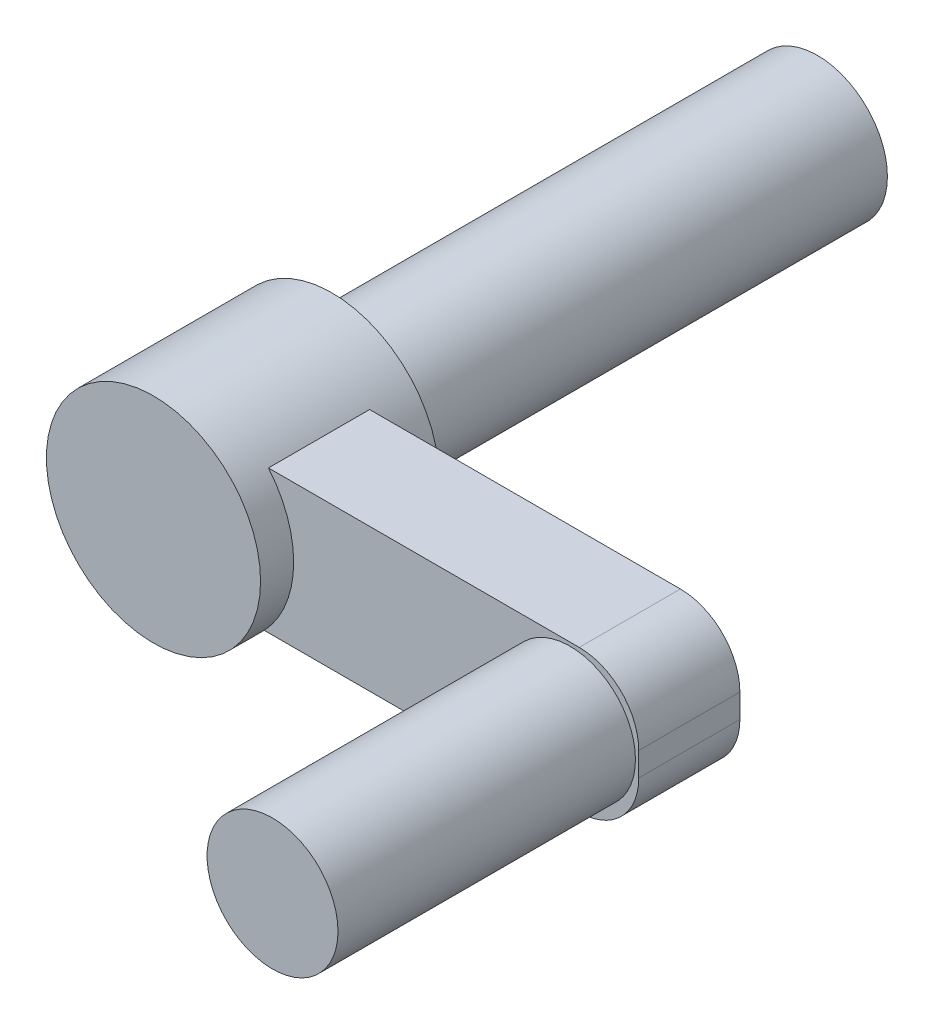
SolidWorks part; units mm, degrees
ref_plane "Front Plane" through (0, 0, 0) normal (0, 0, 1) x (1, 0, 0)
ref_plane "Top Plane" through (0, 0, 0) normal (0, 1, 0) x (1, 0, 0)
ref_plane "Right Plane" through (0, 0, 0) normal (1, 0, 0) x (0, 0, -1)
sketch "Sketch1" plane through (0, 0, 0) normal (0, 0, 1) x (1, 0, 0)
  circle A1 centre (0, 0) radius 5.88
  dimension "D1" = 11.76
extrude "Boss-Extrude1" add sketch "Sketch1" along normal blind 40.8
sketch "Sketch2" plane through (0, 0, 40.8) normal (0, 0, 1) x (1, 0, 0)
  circle A0 centre (0, 0) radius 9
  dimension "D1" = 18
extrude "Boss-Extrude2" add sketch "Sketch2" along normal blind 15 contours A0
sketch "Sketch3" plane through (0, 0, 0) normal (0, 0, -1) x (-1, 0, 0)
  circle A0 centre (0, 0) radius 5
  dimension "D1" = 10
extrude "Cut-Extrude1" cut sketch "Sketch3" against normal blind 40
sketch "Sketch4" plane through (0, 0, 0) normal (1, 0, 0) x (0, 0, -1)
  line L0 (-53.0179, -6.1976) -> (-53.0179, 5.8024)
  line L1 (-53.0179, -6.1976) -> (-44.5179, -6.1976)
  line L2 (-53.0179, 5.8024) -> (-44.5179, 5.8024)
  line L3 (-44.5179, -6.1976) -> (-44.5179, 5.8024)
  line L4 (-53.0179, -6.1976) -> (-44.5179, 5.8024) construction
  line L5 (-53.0179, 5.8024) -> (-44.5179, -6.1976) construction
  point P1 (-48.7679, -0.1976)
  dimension "D1" = 8.5
  dimension "D2" = 12
extrude "Boss-Extrude4" add sketch "Sketch4" along normal blind 38 contours L2 L3 L1 L0
sketch "Sketch5" plane through (0, 0, 53.0179) normal (0, 0, 1) x (1, 0, 0)
  circle A0 centre (32.2227, 0) radius 5.5
  dimension "D1" = 11
extrude "Boss-Extrude5" add sketch "Sketch5" along normal blind 25
fillet "Fillet1" radius 5 1 edges at (38, 5.8024, 48.7679)
fillet "Fillet2" radius 5 1 edges at (38, -6.1976, 48.7679)
